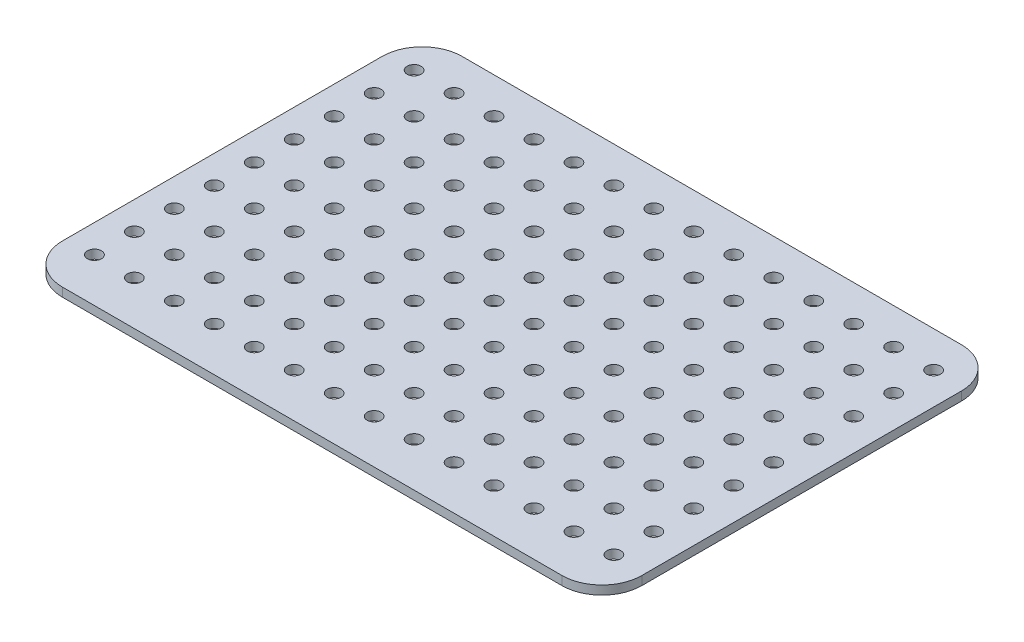
SolidWorks part; units mm, degrees
ref_plane "前视基准面" through (0, 0, 0) normal (0, 0, 1) x (1, 0, 0)
ref_plane "上视基准面" through (0, 0, 0) normal (0, 1, 0) x (1, 0, 0)
ref_plane "右视基准面" through (0, 0, 0) normal (1, 0, 0) x (0, 0, -1)
sketch "草图1" plane through (0, 0, 0) normal (0, 1, 0) x (1, 0, 0)
  line L1 (-72.5, 50) -> (72.5, 50)
  line L2 (-72.5, 50) -> (-72.5, -50)
  line L3 (-72.5, -50) -> (72.5, -50)
  line L4 (72.5, 50) -> (72.5, -50)
  line L5 (-72.5, 50) -> (72.5, -50) construction
  line L6 (-72.5, -50) -> (72.5, 50) construction
  point P0 (0, 0)
  dimension "D1" = 100
  dimension "D2" = 145
extrude "凸台-拉伸1" add sketch "草图1" along normal blind 2.2
sketch "草图2" plane through (0, 2.2, 0) normal (0, 1, 0) x (1, 0, 0)
  line L0 (72.5, 50) -> (-72.5, 50) construction
  line L1 (-72.5, 50) -> (-72.5, -50) construction
  circle A0 centre (-65.5, 41) radius 1.75
  circle A1 centre (-55.5, 41) radius 1.75
  circle A2 centre (-45.5, 41) radius 1.75
  circle A3 centre (-35.5, 41) radius 1.75
  circle A4 centre (-25.5, 41) radius 1.75
  circle A5 centre (-15.5, 41) radius 1.75
  circle A6 centre (-5.5, 41) radius 1.75
  circle A7 centre (4.5, 41) radius 1.75
  circle A8 centre (14.5, 41) radius 1.75
  circle A9 centre (24.5, 41) radius 1.75
  circle A10 centre (34.5, 41) radius 1.75
  circle A11 centre (44.5, 41) radius 1.75
  circle A12 centre (54.5, 41) radius 1.75
  circle A13 centre (64.5, 41) radius 1.75
  circle A14 centre (-55.5, 31) radius 1.75
  circle A15 centre (-45.5, 31) radius 1.75
  circle A16 centre (-35.5, 31) radius 1.75
  circle A17 centre (-25.5, 31) radius 1.75
  circle A18 centre (-15.5, 31) radius 1.75
  circle A19 centre (-5.5, 31) radius 1.75
  circle A20 centre (4.5, 31) radius 1.75
  circle A21 centre (14.5, 31) radius 1.75
  circle A22 centre (24.5, 31) radius 1.75
  circle A23 centre (34.5, 31) radius 1.75
  circle A24 centre (44.5, 31) radius 1.75
  circle A25 centre (54.5, 31) radius 1.75
  circle A26 centre (64.5, 31) radius 1.75
  circle A27 centre (-55.5, 21) radius 1.75
  circle A28 centre (-45.5, 21) radius 1.75
  circle A29 centre (-35.5, 21) radius 1.75
  circle A30 centre (-25.5, 21) radius 1.75
  circle A31 centre (-15.5, 21) radius 1.75
  circle A32 centre (-5.5, 21) radius 1.75
  circle A33 centre (4.5, 21) radius 1.75
  circle A34 centre (14.5, 21) radius 1.75
  circle A35 centre (24.5, 21) radius 1.75
  circle A36 centre (34.5, 21) radius 1.75
  circle A37 centre (44.5, 21) radius 1.75
  circle A38 centre (54.5, 21) radius 1.75
  circle A39 centre (64.5, 21) radius 1.75
  circle A40 centre (-55.5, 11) radius 1.75
  circle A41 centre (-45.5, 11) radius 1.75
  circle A42 centre (-35.5, 11) radius 1.75
  circle A43 centre (-25.5, 11) radius 1.75
  circle A44 centre (-15.5, 11) radius 1.75
  circle A45 centre (-5.5, 11) radius 1.75
  circle A46 centre (4.5, 11) radius 1.75
  circle A47 centre (14.5, 11) radius 1.75
  circle A48 centre (24.5, 11) radius 1.75
  circle A49 centre (34.5, 11) radius 1.75
  circle A50 centre (44.5, 11) radius 1.75
  circle A51 centre (54.5, 11) radius 1.75
  circle A52 centre (64.5, 11) radius 1.75
  circle A53 centre (-55.5, 1) radius 1.75
  circle A54 centre (-45.5, 1) radius 1.75
  circle A55 centre (-35.5, 1) radius 1.75
  circle A56 centre (-25.5, 1) radius 1.75
  circle A57 centre (-15.5, 1) radius 1.75
  circle A58 centre (-5.5, 1) radius 1.75
  circle A59 centre (4.5, 1) radius 1.75
  circle A60 centre (14.5, 1) radius 1.75
  circle A61 centre (24.5, 1) radius 1.75
  circle A62 centre (34.5, 1) radius 1.75
  circle A63 centre (44.5, 1) radius 1.75
  circle A64 centre (54.5, 1) radius 1.75
  circle A65 centre (64.5, 1) radius 1.75
  circle A66 centre (-55.5, -9) radius 1.75
  circle A67 centre (-45.5, -9) radius 1.75
  circle A68 centre (-35.5, -9) radius 1.75
  circle A69 centre (-25.5, -9) radius 1.75
  circle A70 centre (-15.5, -9) radius 1.75
  circle A71 centre (-5.5, -9) radius 1.75
  circle A72 centre (4.5, -9) radius 1.75
  circle A73 centre (14.5, -9) radius 1.75
  circle A74 centre (24.5, -9) radius 1.75
  circle A75 centre (34.5, -9) radius 1.75
  circle A76 centre (44.5, -9) radius 1.75
  circle A77 centre (54.5, -9) radius 1.75
  circle A78 centre (64.5, -9) radius 1.75
  circle A79 centre (-55.5, -19) radius 1.75
  circle A80 centre (-45.5, -19) radius 1.75
  circle A81 centre (-35.5, -19) radius 1.75
  circle A82 centre (-25.5, -19) radius 1.75
  circle A83 centre (-15.5, -19) radius 1.75
  circle A84 centre (-5.5, -19) radius 1.75
  circle A85 centre (4.5, -19) radius 1.75
  circle A86 centre (14.5, -19) radius 1.75
  circle A87 centre (24.5, -19) radius 1.75
  circle A88 centre (34.5, -19) radius 1.75
  circle A89 centre (44.5, -19) radius 1.75
  circle A90 centre (54.5, -19) radius 1.75
  circle A91 centre (64.5, -19) radius 1.75
  circle A92 centre (-55.5, -29) radius 1.75
  circle A93 centre (-45.5, -29) radius 1.75
  circle A94 centre (-35.5, -29) radius 1.75
  circle A95 centre (-25.5, -29) radius 1.75
  circle A96 centre (-15.5, -29) radius 1.75
  circle A97 centre (-5.5, -29) radius 1.75
  circle A98 centre (4.5, -29) radius 1.75
  circle A99 centre (14.5, -29) radius 1.75
  circle A100 centre (24.5, -29) radius 1.75
  circle A101 centre (34.5, -29) radius 1.75
  circle A102 centre (44.5, -29) radius 1.75
  circle A103 centre (54.5, -29) radius 1.75
  circle A104 centre (64.5, -29) radius 1.75
  circle A105 centre (-55.5, -39) radius 1.75
  circle A106 centre (-45.5, -39) radius 1.75
  circle A107 centre (-35.5, -39) radius 1.75
  circle A108 centre (-25.5, -39) radius 1.75
  circle A109 centre (-15.5, -39) radius 1.75
  circle A110 centre (-5.5, -39) radius 1.75
  circle A111 centre (4.5, -39) radius 1.75
  circle A112 centre (14.5, -39) radius 1.75
  circle A113 centre (24.5, -39) radius 1.75
  circle A114 centre (34.5, -39) radius 1.75
  circle A115 centre (44.5, -39) radius 1.75
  circle A116 centre (54.5, -39) radius 1.75
  circle A117 centre (64.5, -39) radius 1.75
  circle A118 centre (-65.5, 31) radius 1.75
  circle A119 centre (-65.5, 21) radius 1.75
  circle A120 centre (-65.5, 11) radius 1.75
  circle A121 centre (-65.5, 1) radius 1.75
  circle A122 centre (-65.5, -9) radius 1.75
  circle A123 centre (-65.5, -19) radius 1.75
  circle A124 centre (-65.5, -29) radius 1.75
  circle A125 centre (-65.5, -39) radius 1.75
  dimension "D1" = 3.5
  dimension "D2" = 9
  dimension "D3" = 7
  dimension "D4" = 14
  dimension "D5" = 9
extrude "切除-拉伸1" cut sketch "草图2" against normal blind 2.5
fillet "圆角1" radius 10 4 edges at (-72.5, 1.1, 50) (72.5, 1.1, 50) (72.5, 1.1, -50) (-72.5, 1.1, -50)
